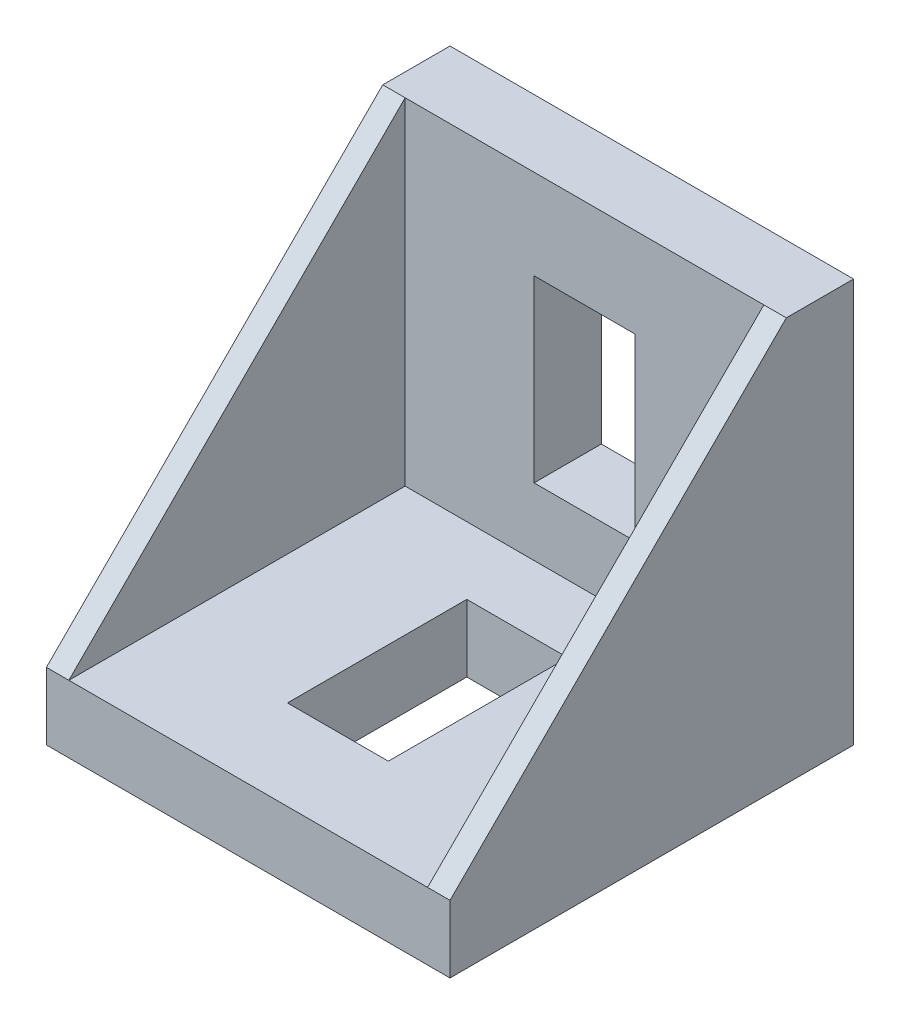
SolidWorks part; units mm, degrees
ref_plane "Front Plane" through (0, 0, 0) normal (0, 0, 1) x (1, 0, 0)
ref_plane "Top Plane" through (0, 0, 0) normal (0, 1, 0) x (1, 0, 0)
ref_plane "Right Plane" through (0, 0, 0) normal (1, 0, 0) x (0, 0, -1)
sketch "Sketch1" plane through (0, 0, 0) normal (0, 1, 0) x (1, 0, 0)
  line L1 (-9, -9) -> (9, -9)
  line L2 (-9, -9) -> (-9, 9)
  line L3 (-9, 9) -> (9, 9)
  line L4 (9, -9) -> (9, 9)
  line L5 (-9, -9) -> (9, 9) construction
  line L6 (-9, 9) -> (9, -9) construction
  point P0 (0, 0)
  dimension "D1" = 18
  dimension "D2" = 18
extrude "Boss-Extrude1" add sketch "Sketch1" along normal blind 3
sketch "Sketch3" plane through (0, 0, 0) normal (0, -1, 0) x (1, 0, 0)
  line L0 (9, -9) -> (-9, -9) construction
  line L1 (-2.25, 5) -> (2.25, 5)
  line L2 (-2.25, 5) -> (-2.25, -3)
  line L3 (-2.25, -3) -> (2.25, -3)
  line L4 (2.25, 5) -> (2.25, -3)
  line L5 (0, 9) -> (0, -9) construction
  line L6 (-9, 9) -> (9, 9) construction
  point P10 (0, 5)
  dimension "D1" = 4.5
  dimension "D2" = 8
  dimension "D3" = 6
extrude "Cut-Extrude1" cut sketch "Sketch3" against normal through all contours L2 L1 L4 L3
sketch "Sketch6" plane through (0, 3, 0) normal (0, 1, 0) x (1, 0, 0)
  line L0 (9, -9) -> (9, 9) construction
  line L1 (-9, 9) -> (9, 9)
  line L2 (-9, 9) -> (-9, 6)
  line L3 (-9, 6) -> (9, 6)
  line L4 (9, 9) -> (9, 6)
  dimension "D1" = 3
extrude "Boss-Extrude3" add sketch "Sketch6" along normal blind 15 contours L2 L1 L4 L3
sketch "Sketch7" plane through (0, 0, -9) normal (0, 0, -1) x (-1, 0, 0)
  line L0 (0, 18) -> (0, 0) construction
  line L1 (-2.25, 14) -> (2.25, 14)
  line L2 (-2.25, 14) -> (-2.25, 6)
  line L3 (-2.25, 6) -> (2.25, 6)
  line L4 (2.25, 14) -> (2.25, 6)
  line L5 (9, 18) -> (-9, 18) construction
  point P10 (0, 14)
  dimension "D1" = 4.5
  dimension "D2" = 8
  dimension "D3" = 6
extrude "Cut-Extrude2" cut sketch "Sketch7" against normal through all contours L2 L1 L4 L3
sketch "Sketch9" plane through (-9, 0, 0) normal (-1, 0, 0) x (0, 0, 1)
  line L0 (-6, 18) -> (9, 3)
  line L1 (9, 3) -> (-6, 3)
  line L2 (-6, 3) -> (-6, 18)
extrude "Boss-Extrude4" add sketch "Sketch9" against normal blind 1 contours L2 L0 L1
ref_plane "Plane1" through (0, 0, 0) normal (-1, 0, 0) x (0, 0, 1)
mirror "Mirror1" about plane through (0, 0, 0) normal (-1, 0, 0) of "Boss-Extrude1", "Boss-Extrude4"
sketch "Sketch10" plane through (0, 0, 0) normal (0, -1, 0) x (1, 0, 0)
  line L0 (9, -9) -> (-9, -9) construction
  line L1 (-2.25, 5) -> (2.25, 5)
  line L2 (-2.25, 5) -> (-2.25, -3)
  line L3 (-2.25, -3) -> (2.25, -3)
  line L4 (2.25, 5) -> (2.25, -3)
  line L5 (0, 9) -> (0, -9) construction
  line L6 (-9, 9) -> (9, 9) construction
  point P10 (0, 5)
  dimension "D1" = 4.5
  dimension "D2" = 8
  dimension "D3" = 6
extrude "Cut-Extrude3" cut sketch "Sketch10" against normal up to next
